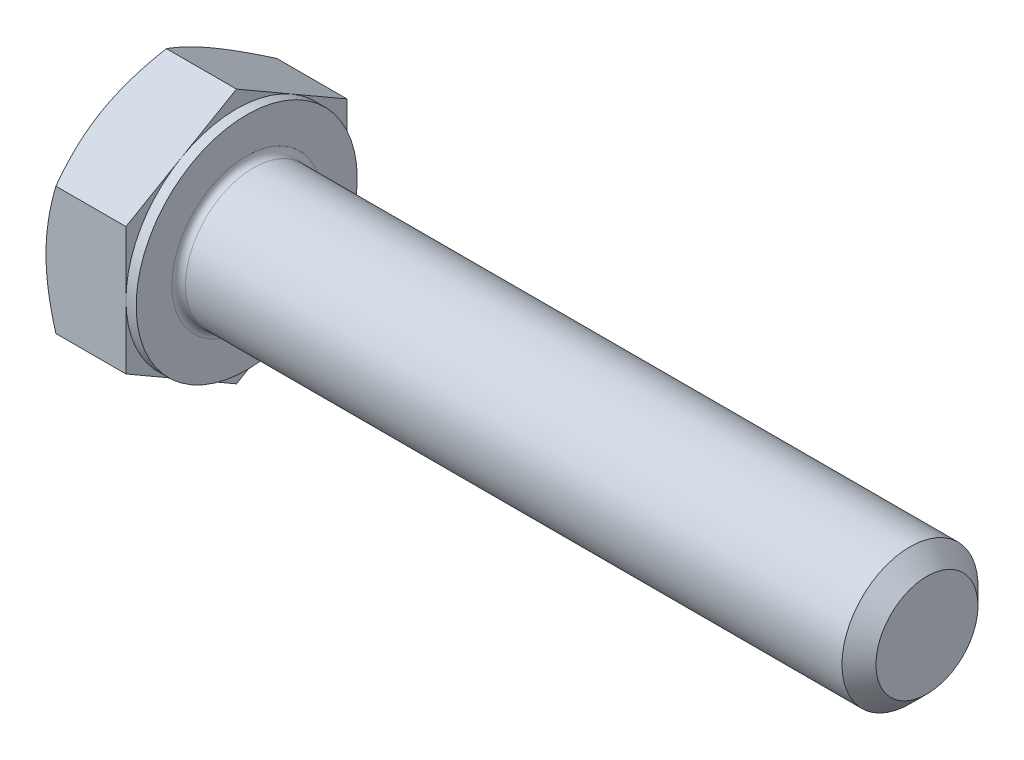
SolidWorks part; units mm, degrees
extrude "基体-拉伸" add sketch "草图1" along normal blind 5.3
sketch "草图1" plane through (0, 0, 0) normal (1, 0, 0) x (0, 0, -1)
  line L0 (6.5, 3.7528) -> (6.5, -3.7528)
  line L1 (-6.5, 3.7528) -> (-6.5, -3.7528)
  line L2 (6.5, -3.7528) -> (0, -7.5056)
  line L3 (0, -7.5056) -> (-6.5, -3.7528)
  line L4 (6.5, 3.7528) -> (0, 7.5056)
  line L5 (0, 7.5056) -> (-6.5, 3.7528)
  dimension "s" = 13
  dimension "D2" = 120
  dimension "D3" = 6.5
  dimension "D4" = 6.5
  dimension "D5" = 6.5
revolve "切除-旋转1" cut sketch "草图3" angle 360 about L6
sketch "草图3" plane through (0, 0, 0) normal (0, 0, 1) x (1, 0, 0)
  line L0 (0, 6.5) -> (3.4673, 12.5056)
  line L1 (0, 7.5056) -> (0, 3.7528) construction
  line L2 (3.4673, 12.5056) -> (3.4673, 17.5056)
  line L3 (3.4673, 17.5056) -> (-10, 17.5056)
  line L4 (-10, 17.5056) -> (-10, 6.5)
  line L5 (-10, 6.5) -> (0, 6.5)
  line L6 (0, 0) -> (99.06, 0) construction
  line L7 (5.3, 7.5056) -> (0, 7.5056) construction
  dimension "D1" = 6.5
  dimension "D2" = 5
  dimension "D3" = 10
  dimension "D4" = 5
  dimension "Head_ch_ang" = 30
material "3.6级"
ref_plane "前视" through (0, 0, 0) normal (0, 0, 1) x (1, 0, 0)
ref_plane "上视" through (0, 0, 0) normal (0, 1, 0) x (1, 0, 0)
ref_plane "右视" through (0, 0, 0) normal (1, 0, 0) x (0, 0, -1)
sketch "草图2" plane through (0, 0, 0) normal (0, 0, 1) x (1, 0, 0)
  line L0 (0, 3.7528) -> (0, -3.7528) construction
  line L1 (0, 0) -> (45.3, 0)
  line L2 (0, 0) -> (0, 4)
  line L3 (0, 4) -> (27.8072, 4)
  line L4 (45.3, 0) -> (45.3, 2.9175)
  line L5 (5.3, 7.5056) -> (5.3, 3.7528) construction
  line L7 (0, 0) -> (96.52, 0) construction
  line L8 (45.3, -2.9175) -> (27.8072, -4) construction
  line L9 (0, -4) -> (27.8072, -4) construction
  line L10 (6.55, 15.24) -> (6.55, -1.27) construction
  line L11 (30.3, 15.24) -> (30.3, -1.27) construction
  line L12 (5.3, 3.7528) -> (5.3, -3.7528) construction
  line L13 (27.8072, 4) -> (45.3, 4)
  line L14 (45.3, 4) -> (45.3, 2.9175)
revolve "凸台-旋转1" add sketch "草图2" angle 360 about L7
cosmetic thread "螺旋线1" parameters "Thread_length"=15, "Thread_minor"=5.835
sketch "草图5" plane through (0, 0, 0) normal (0, 0, 1) x (1, 0, 0)
  line L0 (5.3, 6.5) -> (1.8327, 12.5056)
  line L1 (5.3, 7.5056) -> (5.3, 3.7528) construction
  line L2 (1.8327, 12.5056) -> (1.8327, 17.5056)
  line L3 (1.8327, 17.5056) -> (11.8327, 17.5056)
  line L4 (11.8327, 17.5056) -> (11.8327, 6.5)
  line L5 (11.8327, 6.5) -> (5.3, 6.5)
  line L7 (5.3, 7.5056) -> (0.5806, 7.5056) construction
  line L8 (0, 0) -> (99.06, 0) construction
  line L9 (0, 0) -> (99.06, 0) construction
  dimension "D1" = 6.5
  dimension "D2" = 5
  dimension "D3" = 10
  dimension "D4" = 5
  dimension "Head_ch_ang" = 30
revolve "切除-旋转2" cut sketch "草图5" angle 360 about L8
sketch "草图4" plane through (0, 0, 0) normal (0, 0, 1) x (1, 0, 0)
  line L1 (5.3, 7.5056) -> (5.3, 3.7528) construction
  line L2 (5.3, 6.5) -> (4.7, 6.5)
  line L3 (5.3, 6.5) -> (5.3, 17.5056)
  line L4 (5.3, 17.5056) -> (4.7, 17.5056)
  line L5 (0, 0) -> (95.25, 0) construction
  line L6 (0, 0) -> (96.52, 0) construction
  line L7 (4.7, 6.5) -> (4.7, 17.5056)
  line L8 (4.7194, 7.5056) -> (0.5806, 7.5056) construction
  dimension "D2" = 10
  dimension "D1" = 13
revolve "切除-旋转3" cut sketch "草图4" angle 360 about L5
chamfer "倒角" distance 1 angle 45 1 edges at (45.3, 0, 4)
fillet "圆角" radius 0.4 1 edges at (5.3, 0, -4)
sketch "草图6" plane through (0, 0, 0) normal (0, 0, 1) x (1, 0, 0)
  line L0 (30.3, -2.9175) -> (29.675, -4)
  line L1 (30.3, -2.9175) -> (30.925, -4)
  line L2 (30.925, -4) -> (30.925, -5)
  line L3 (-3.175, 0) -> (5.1513, 0) construction
  line L5 (30.925, -5) -> (29.675, -5)
  line L6 (29.675, -5) -> (29.675, -4)
  dimension "Thread_minor" = 5.835
  dimension "Diameter" = 8
  dimension "Start" = 30.3
revolve "切除-旋转4" [suppressed] cut sketch "草图6" angle 360 about L3
pattern_linear "阵列(线性)1" [suppressed]
equation "\"D3@草图1\" = \"s@草图1\" / 2"
equation "\"D4@草图1\" = \"D3@草图1\""
equation "\"D5@草图1\" = \"D4@草图1\""
equation "\"Thread_minor@螺旋线1\" = \"Minor_dia@草图2\""
equation "\"D1@草图3\" = \"s@草图1\" / 2"
equation "\"D1@草图5\" = \"s@草图1\" / 2"
equation "\"Head_ch_ang@草图5\" = \"Head_ch_ang@草图3\""
equation "\"D1@草图4\" = \"s@草图1\""
equation "\"Thread_length@螺旋线1\" = ((sgn( (\"l@草图2\" - \"p@草图2\" ) - \"h@草图2\" )-1)*( (\"l@草图2\" - \"p@草图2\" ) - \"h@草图2\" ))/-2+ \"h@草图2\""
equation "\"Thread_minor@草图6\" = \"Minor_dia@草图2\""
equation "\"Diameter@草图6\" = \"m@草图2\""
equation "\"Overcut@草图6\" = \"m@草图2\" * 1.25"
equation "\"Start@草图6\" = \"k@基体-拉伸\" + \"l@草图2\" - \"Thread_length@螺旋线1\"  '---Non-countersunk---"
equation "\"Num_threads@阵列(线性)1\" = int( \"Thread_length@螺旋线1\" / \"p@草图2\" + 0.999 )  + 1"
equation "\"Advance@阵列(线性)1\" = \"Thread_length@螺旋线1\" /  (\"Num_threads@阵列(线性)1\" - 1) 'relax it"
equation "\"Num_threads@阵列(线性)1\" = \"Num_threads@阵列(线性)1\" - sgn( \"Num_threads@阵列(线性)1\" - 1) '---chamfered tips only---"
equation "\"Minor_dia@草图2\" = \"m@草图2\"-\"p@草图2\" * 1.732"
equation "\"D1@倒角\" = \"p@草图2\"*0.8"
